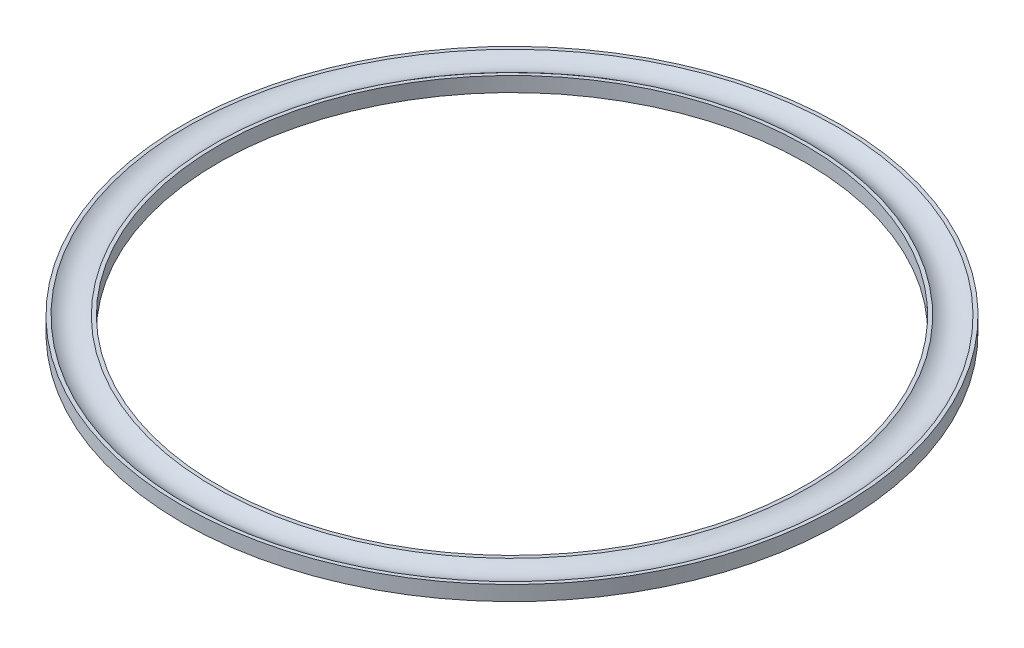
SolidWorks part; units mm, degrees
ref_plane "Front" through (0, 0, 0) normal (0, 0, 1) x (1, 0, 0)
ref_plane "Top" through (0, 0, 0) normal (0, 1, 0) x (1, 0, 0)
ref_plane "Right" through (0, 0, 0) normal (1, 0, 0) x (0, 0, -1)
sketch "Sketch1" plane through (0, 0, 0) normal (0, 0, 1) x (1, 0, 0)
  line L0 (-38.3286, 0) -> (38.3286, 0) construction
  line L1 (42.9768, -0.9652) -> (42.9768, 0.9652)
  line L2 (42.9768, 0.9652) -> (38.3286, 0.9652) construction
  line L3 (0, -11.4126) -> (0, 23.1775) construction
  line L4 (0, -0.6845) -> (0, 0.6845) construction
  line L5 (38.3286, 0.9652) -> (38.7934, 0.9652)
  line L6 (42.9768, -0.9652) -> (38.3286, -0.9652)
  line L7 (38.3286, 0.9652) -> (38.3286, -0.9652)
  line L8 (42.9768, 0.9652) -> (42.512, 0.9652)
  arc A0 (38.7934, 0.9652) -> (42.512, 0.9652) centre (40.6527, 3.2298) ccw
  point P4 (38.3286, 0)
  point P13 (40.6527, 0.2997)
  dimension "D1" = 0.6655
  dimension "D2" = 0.4648
revolve "Revolve2" add sketch "Sketch1" angle 360 about L3
sketch "Sketch3" plane through (0, -0.9652, 0) normal (0, -1, 0) x (1, 0, 0)
  line L0 (38.3286, 0) -> (-38.3286, 0) construction
  circle A0 centre (0, 0) radius 38.3286 construction
  dimension "D1" = 76.6572
equation "\"D2@Sketch1\" = \"Wd@Sketch1\"/10"
